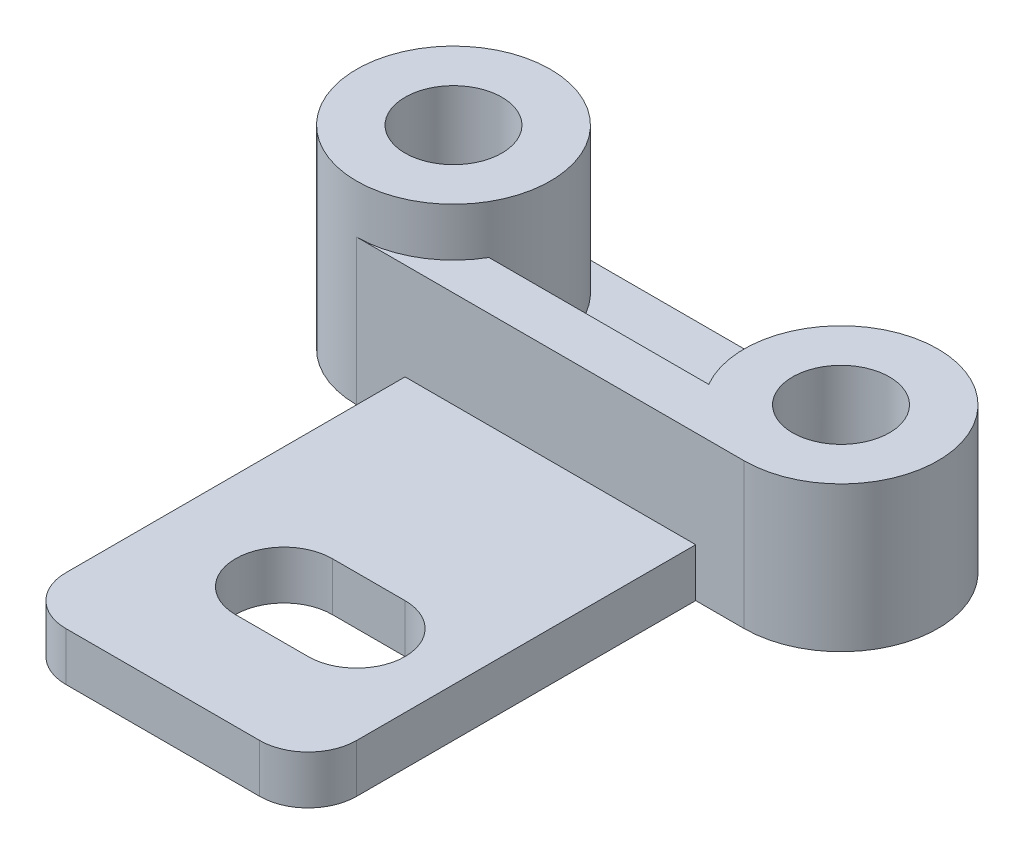
SolidWorks part; units mm, degrees
ref_plane "Front Plane" through (0, 0, 0) normal (0, 0, 1) x (1, 0, 0)
ref_plane "Top Plane" through (0, 0, 0) normal (0, 1, 0) x (1, 0, 0)
ref_plane "Right Plane" through (0, 0, 0) normal (1, 0, 0) x (0, 0, -1)
sketch "Sketch1" plane through (0, 0, 0) normal (0, 1, 0) x (1, 0, 0)
  circle A0 centre (0, 0) radius 20
  dimension "D1" = 40
extrude "Boss-Extrude1" add sketch "Sketch1" along normal blind 40
sketch "Sketch2" plane through (0, 40, 0) normal (0, 1, 0) x (1, 0, 0)
  circle A0 centre (0, 0) radius 10
  dimension "D1" = 20
extrude "Cut-Extrude1" cut sketch "Sketch2" against normal through all
sketch "Sketch3" plane through (0, 0, 0) normal (0, 1, 0) x (1, 0, 0)
  circle A0 centre (80, 0) radius 20
  circle A1 centre (0, 0) radius 20 construction
  dimension "D1" = 80
extrude "Boss-Extrude2" add sketch "Sketch3" along normal blind 30 separate body
sketch "Sketch4" plane through (0, 30, 0) normal (0, 1, 0) x (1, 0, 0)
  circle A0 centre (80, 0) radius 10
  circle A1 centre (80, 0) radius 20 construction
  circle A3 centre (0, 0) radius 10 construction
extrude "Cut-Extrude2" cut sketch "Sketch4" against normal through all
sketch "Sketch5" plane through (0, 30, 0) normal (0, 1, 0) x (1, 0, 0)
  line L0 (0, -20) -> (80, -20)
  line L1 (0, -10) -> (80, -10)
  line L2 (80, -10) -> (80, -20)
  line L3 (0, -10) -> (0, -20)
  circle A0 centre (0, 0) radius 20 construction
  circle A1 centre (80, 0) radius 20 construction
  circle A2 centre (80, 0) radius 10 construction
  circle A4 centre (0, 0) radius 10 construction
  dimension "D1" = 10
extrude "Boss-Extrude3" add sketch "Sketch5" against normal blind 30
sketch "Sketch6" plane through (0, 0, 0) normal (0, -1, 0) x (1, 0, 0)
  line L0 (0, 0) -> (80, 0) construction
  line L1 (0, 20) -> (80, 20)
  line L2 (0, -20) -> (80, -20)
  arc A0 (0, 20) -> (0, -20) centre (0, 0) ccw
  arc A1 (80, -20) -> (80, 20) centre (80, 0) ccw
  arc A3 (0, 20) -> (17.3205, 10) centre (0, 0) ccw construction
  point P2 (40, 0)
  dimension "D1" = 20
  dimension "D2" = 80
extrude "Boss-Extrude4" add sketch "Sketch6" against normal blind 10
sketch "Sketch7" plane through (0, 0, 0) normal (0, 1, 0) x (1, 0, 0)
  line L0 (0, -20) -> (80, -20) construction
  line L1 (10, -20) -> (70, -20)
  line L2 (10, -20) -> (10, -90)
  line L3 (20, -100) -> (60, -100)
  line L4 (70, -20) -> (70, -90)
  line L5 (35, -70) -> (50, -70) construction
  line L6 (35, -60) -> (50, -60)
  line L7 (35, -80) -> (50, -80)
  arc A0 (60, -100) -> (70, -90) centre (60, -90) ccw
  arc A1 (10, -90) -> (20, -100) centre (20, -90) ccw
  arc A2 (35, -60) -> (35, -80) centre (35, -70) ccw
  arc A3 (50, -80) -> (50, -60) centre (50, -70) ccw
  point P9 (70, -100)
  point P12 (10, -100)
  point P15 (42.5, -70)
  dimension "D3" = 10
  dimension "D6" = 10
  dimension "D1" = 60
  dimension "D2" = 100
  dimension "D4" = 10
  dimension "D5" = 30
  dimension "D7" = 15
  dimension "D8" = 20
extrude "Boss-Extrude5" add sketch "Sketch7" along normal blind 10
